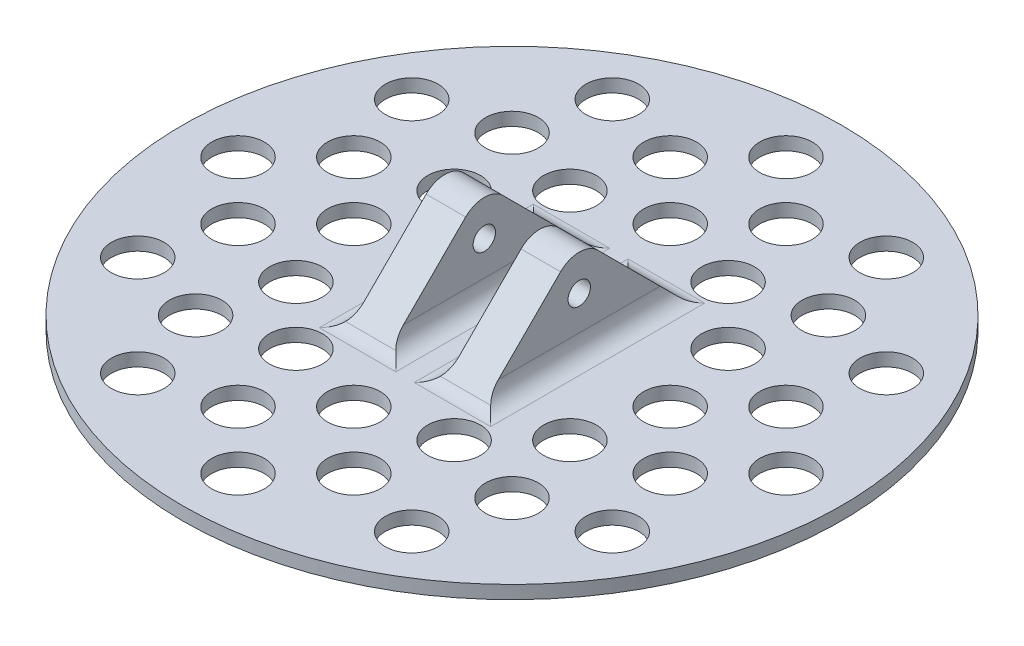
SolidWorks part; units mm, degrees
ref_plane "Front Plane" through (0, 0, 0) normal (0, 0, 1) x (1, 0, 0)
ref_plane "Top Plane" through (0, 0, 0) normal (0, 1, 0) x (1, 0, 0)
ref_plane "Right Plane" through (0, 0, 0) normal (1, 0, 0) x (0, 0, -1)
sketch "Sketch1" plane through (0, 0, 0) normal (0, 1, 0) x (1, 0, 0)
  circle A0 centre (0, 0) radius 125
  dimension "D1" = 250
extrude "Boss-Extrude1" add sketch "Sketch1" against normal blind 5
ref_plane "Plane1" through (10.5, 0, 0) normal (1, 0, 0) x (0, 0, -1)
sketch "Sketch4" plane through (10.5, 0, 0) normal (1, 0, 0) x (0, 0, -1)
  line L0 (37.6777, 0) -> (-37.6777, 0)
  line L1 (125, 0) -> (-125, 0) construction
  line L2 (-37.6777, 0) -> (-7.0711, 30.6066)
  line L3 (7.0711, 30.6066) -> (37.6777, 0)
  line L4 (0, 0) -> (0, 20) construction
  circle A1 centre (0, 20) radius 12.5 construction
  circle A2 centre (0, 20) radius 4.25
  arc A3 (-7.0711, 30.6066) -> (7.0711, 30.6066) centre (0, 23.5355) cw
  point P5 (0, 0)
  dimension "D1" = 20
  dimension "D2" = 25
  dimension "D3" = 8.5
  dimension "D4" = 10
extrude "Boss-Extrude2" add sketch "Sketch4" along normal blind 15
fillet "Fillet1" radius 7 4 edges at (10.5, 0, 0) (18, 0, 37.6777) (18, 0, -37.6777) (25.5, 0, 0)
mirror "Mirror1" about plane through (0, 0, 0) normal (1, 0, 0) of "Fillet1", "Boss-Extrude2"
sketch "Sketch5" plane through (0, 0, 0) normal (0, 1, 0) x (1, 0, 0)
  line L0 (0, 0) -> (-60, 0) construction
  line L7 (-60, 0) -> (-51.9615, 30) construction
  line L8 (-51.9615, 30) -> (-81.9615, 21.9615) construction
  line L9 (-81.9615, 21.9615) -> (-60, 0) construction
  line L15 (-60, 0) -> (-103.923, 0) construction
  line L16 (-103.923, 0) -> (-81.9615, 21.9615) construction
  circle A3 centre (-60, 0) radius 10
  circle A4 centre (-51.9615, 30) radius 10
  circle A5 centre (-30, 51.9615) radius 10
  circle A6 centre (0, 60) radius 10
  circle A7 centre (30, 51.9615) radius 10
  circle A8 centre (51.9615, 30) radius 10
  circle A9 centre (60, 0) radius 10
  circle A10 centre (51.9615, -30) radius 10
  circle A11 centre (30, -51.9615) radius 10
  circle A12 centre (0, -60) radius 10
  circle A13 centre (-30, -51.9615) radius 10
  circle A14 centre (-51.9615, -30) radius 10
  circle A15 centre (-81.9615, 21.9615) radius 10
  circle A16 centre (-60, 60) radius 10
  circle A17 centre (-21.9615, 81.9615) radius 10
  circle A18 centre (21.9615, 81.9615) radius 10
  circle A19 centre (60, 60) radius 10
  circle A20 centre (81.9615, 21.9615) radius 10
  circle A21 centre (81.9615, -21.9615) radius 10
  circle A22 centre (60, -60) radius 10
  circle A23 centre (21.9615, -81.9615) radius 10
  circle A24 centre (-21.9615, -81.9615) radius 10
  circle A25 centre (-60, -60) radius 10
  circle A26 centre (-81.9615, -21.9615) radius 10
  circle A27 centre (-103.923, 0) radius 10
  circle A28 centre (-90, 51.9615) radius 10
  circle A29 centre (-51.9615, 90) radius 10
  circle A30 centre (0, 103.923) radius 10
  circle A31 centre (51.9615, 90) radius 10
  circle A32 centre (90, 51.9615) radius 10
  circle A33 centre (103.923, 0) radius 10
  circle A34 centre (90, -51.9615) radius 10
  circle A35 centre (51.9615, -90) radius 10
  circle A36 centre (0, -103.923) radius 10
  circle A37 centre (-51.9615, -90) radius 10
  circle A38 centre (-90, -51.9615) radius 10
  point P31 (0, 0)
  point P56 (0, 0)
  point P79 (0, 0)
  dimension "D2" = 20
  dimension "D1" = 60
  dimension "D3" = 12
  dimension "D4" = 12
  dimension "D5" = 12
extrude "Cut-Extrude1" cut sketch "Sketch5" against normal blind 15
